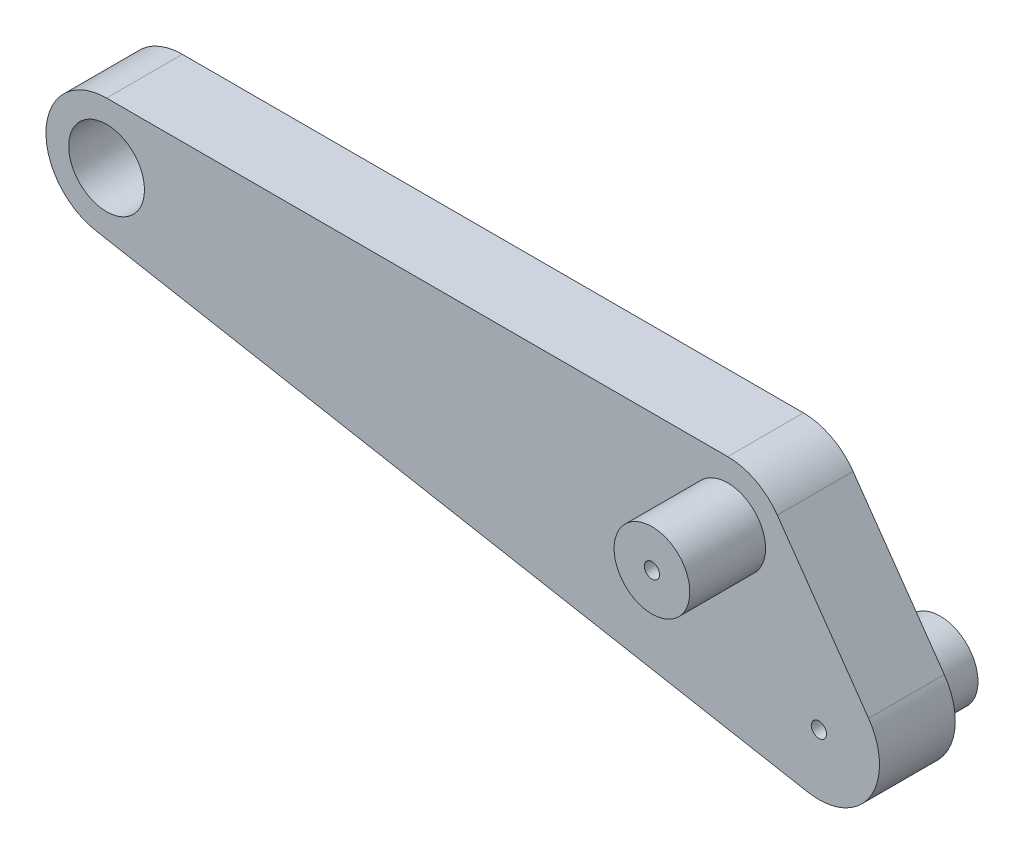
SolidWorks part; units mm, degrees
material "ABS"
ref_plane "Front Plane" through (0, 0, 0) normal (0, 0, 1) x (1, 0, 0)
ref_plane "Top Plane" through (0, 0, 0) normal (0, 1, 0) x (1, 0, 0)
ref_plane "Right Plane" through (0, 0, 0) normal (1, 0, 0) x (0, 0, -1)
sketch "Sketch1" plane through (0, 0, 0) normal (0, 0, 1) x (1, 0, 0)
  line L0 (0, 0) -> (-41, 0)
  line L1 (0, 0) -> (6.0226, -8.6011)
  dimension "D1" = 41
  dimension "D2" = 10.5
  dimension "D3" = 125
sketch "Sketch2" plane through (0, 0, 0) normal (0, 0, 1) x (1, 0, 0)
  line L0 (-41, 4) -> (0, 4)
  line L1 (3.2766, 2.2943) -> (9.2992, -6.3068)
  line L2 (5.3028, -12.5358) -> (-41.7197, -3.9347)
  circle A0 centre (-41, 0) radius 2.5
  arc A1 (-41, 4) -> (-41.7197, -3.9347) centre (-41, 0) ccw
  circle A2 centre (0, 0) radius 2.5
  arc A3 (3.2766, 2.2943) -> (0, 4) centre (0, 0) ccw
  circle A4 centre (6.0226, -8.6011) radius 2.5
  arc A5 (5.3028, -12.5358) -> (9.2992, -6.3068) centre (6.0226, -8.6011) ccw
  dimension "D1" = 5
  dimension "D2" = 8
  dimension "D3" = 5
  dimension "D4" = 8
  dimension "D5" = 5
  dimension "D6" = 8
extrude "Boss-Extrude1" add sketch "Sketch2" along normal blind 5
sketch "Sketch3" plane through (0, 0, 5) normal (0, 0, 1) x (1, 0, 0)
  circle A0 centre (6.0226, -8.6011) radius 2.5
  circle A1 centre (6.0226, -8.6011) radius 0.5
  dimension "D1" = 1
  dimension "D2" = 5
extrude "Boss-Extrude2" add sketch "Sketch3" against normal blind 8
sketch "Sketch4" plane through (0, 0, 0) normal (0, 0, -1) x (-1, 0, 0)
  circle A0 centre (0, 0) radius 2.5
  circle A1 centre (0, 0) radius 0.5
  dimension "D1" = 1
  dimension "D2" = 5
extrude "Boss-Extrude3" add sketch "Sketch4" against normal blind 10
